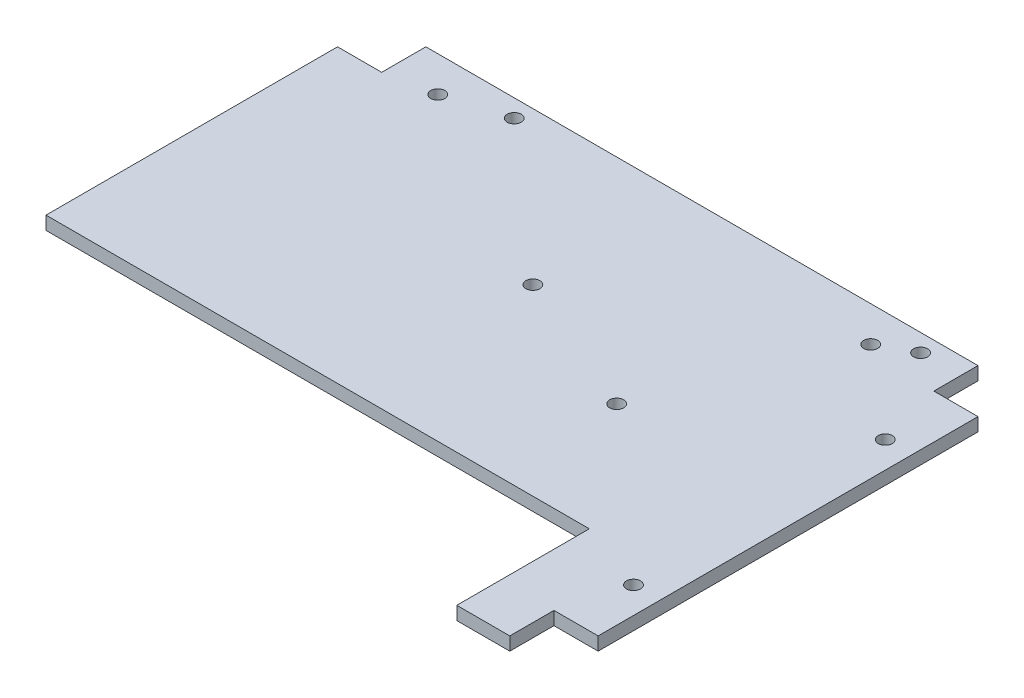
SolidWorks part; units mm, degrees
ref_plane "Front Plane" through (0, 0, 0) normal (0, 0, 1) x (1, 0, 0)
ref_plane "Top Plane" through (0, 0, 0) normal (0, 1, 0) x (1, 0, 0)
ref_plane "Right Plane" through (0, 0, 0) normal (1, 0, 0) x (0, 0, -1)
sketch "Sketch1" plane through (0, 0, 0) normal (0, 1, 0) x (1, 0, 0)
  line L0 (0, 0) -> (-145, 0) construction
  line L1 (0, 0) -> (0, -106) construction
  line L2 (-145, 0) -> (-145, -76) construction
  line L3 (-145, -76) -> (-22, -76)
  line L4 (0, -106) -> (-22, -106) construction
  line L5 (-22, -76) -> (-22, -106)
  line L6 (0, 0) -> (0, -10) construction
  line L7 (0, 0) -> (-10, 0) construction
  line L8 (-145, 0) -> (-135, 0) construction
  line L9 (-135, 0) -> (-10, 0)
  line L10 (-10, 0) -> (-10, -10)
  line L11 (-10, -10) -> (0, -10)
  line L12 (-135, 0) -> (-135, -10)
  line L13 (-135, -10) -> (-145, -10)
  line L14 (-145, -10) -> (-145, -76)
  line L15 (0, -106) -> (0, -96) construction
  line L16 (-22, -106) -> (-10, -106)
  line L17 (-10, -106) -> (-10, -96)
  line L18 (-10, -96) -> (0, -96)
  line L19 (0, -96) -> (0, -10)
extrude "Extrude1" add sketch "Sketch1" along normal blind 3
sketch "Sketch2" plane through (0, 3, 0) normal (0, 1, 0) x (1, 0, 0)
  line L0 (0, -10) -> (-6, -10) construction
  line L2 (0, -10) -> (-10, -10) construction
  line L3 (-6, -10) -> (-6, -25) construction
  line L4 (-6, -25) -> (-6, -82) construction
  line L5 (-10, 0) -> (-10, -8) construction
  line L6 (-10, -10) -> (-10, 0) construction
  line L7 (-10, -8) -> (-26.3, -8) construction
  line L8 (-26.3, -8) -> (-124.3, -8) construction
  circle A0 centre (-6, -25) radius 1.5875
  circle A1 centre (-6, -82) radius 1.5875
  circle A2 centre (-26.3, -8) radius 1.5875
  circle A3 centre (-124.3, -8) radius 1.5875
extrude "Extrude2" cut sketch "Sketch2" against normal up to surface (3 mm away) up to face at (-53.6667, 0, 49.6667)
sketch "Sketch3" plane through (0, 3, 0) normal (0, 1, 0) x (1, 0, 0)
  line L0 (-10, 0) -> (-19, 0) construction
  line L1 (-10, 0) -> (-135, 0) construction
  line L2 (-19, 0) -> (-19, -4) construction
  line L3 (-19, 0) -> (-111, 0) construction
  line L4 (-111, 0) -> (-111, -4) construction
  line L5 (-19, -4) -> (-19, -48.4) construction
  line L6 (-19, -48.4) -> (-43.4, -48.4) construction
  circle A0 centre (-111, -4) radius 1.5875
  circle A1 centre (-19, -4) radius 1.5875
  circle A2 centre (-43.4, -48.4) radius 1.5875
extrude "Extrude3" cut sketch "Sketch3" against normal up to surface (3 mm away) up to face at (-124.3, 0, 6.4125)
sketch "Sketch5" plane through (0, 3, 0) normal (0, 1, 0) x (1, 0, 0)
  line L0 (34.3227, -34.524) -> (-145, -34.524) construction
  line L1 (-145, -10) -> (-145, -76) construction
  line L2 (-111, -4) -> (-19, -4) construction
  line L3 (-65, -4) -> (-65, -34.524) construction
  line L4 (-65, -34.524) -> (-76.25, -34.524) construction
  circle A0 centre (-76.25, -34.524) radius 1.5875
extrude "Cut-Extrude1" cut sketch "Sketch5" against normal up to surface (3 mm away) up to face at (-43.4, 0, 46.8125)
